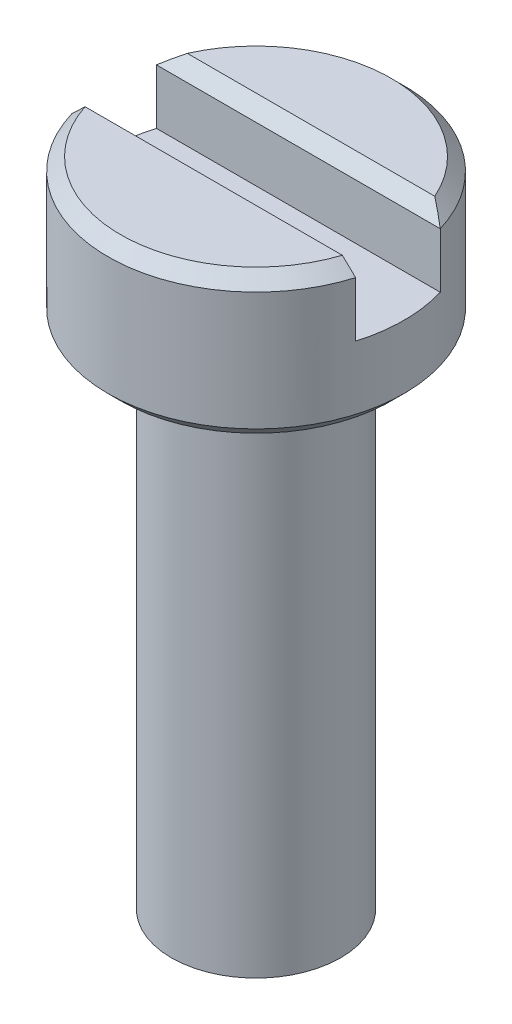
SolidWorks part; units mm, degrees
ref_plane "Front Plane" through (0, 0, 0) normal (0, 0, 1) x (1, 0, 0)
ref_plane "Top Plane" through (0, 0, 0) normal (0, 1, 0) x (1, 0, 0)
ref_plane "Right Plane" through (0, 0, 0) normal (1, 0, 0) x (0, 0, -1)
sketch "Sketch1" plane through (0, 0, 0) normal (0, 1, 0) x (1, 0, 0)
  circle A0 centre (0, 0) radius 1.75
  dimension "D1" = 3.5
extrude "Boss-Extrude1" add sketch "Sketch1" along normal blind 1.7
sketch "Sketch2" plane through (0, 0, 0) normal (0, -1, 0) x (1, 0, 0)
  circle A0 centre (0, 0) radius 1
  dimension "D1" = 2
extrude "Boss-Extrude2" add sketch "Sketch2" along normal blind 6
sketch "Sketch4" plane through (0, 1.7, 0) normal (0, 1, 0) x (1, 0, 0)
  line L1 (2, -0.5) -> (-2, -0.5)
  line L2 (2, -0.5) -> (2, 0.5)
  line L3 (2, 0.5) -> (-2, 0.5)
  line L4 (-2, -0.5) -> (-2, 0.5)
  line L5 (2, -0.5) -> (-2, 0.5) construction
  line L6 (2, 0.5) -> (-2, -0.5) construction
  point P0 (0, 0)
  dimension "D1" = 4
  dimension "D2" = 1
extrude "Cut-Extrude1" cut sketch "Sketch4" against normal blind 0.8
chamfer "Chamfer1" distance 0.15 angle 45 4 edges at (0, 1.7, -1.75) (0, 1.7, -0.5) (0, 1.7, 1.75) (0, 0, 1.75)
fillet "Fillet1" radius 0.2 1 edges at (0, 0, -1)
